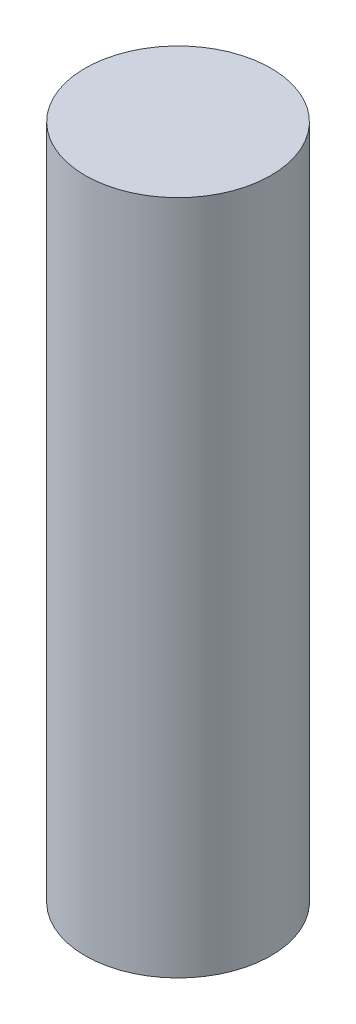
SolidWorks part; units mm, degrees
material "PBT General Purpose"
ref_plane "Front Plane" through (0, 0, 0) normal (0, 0, 1) x (1, 0, 0)
ref_plane "Top Plane" through (0, 0, 0) normal (0, 1, 0) x (1, 0, 0)
ref_plane "Right Plane" through (0, 0, 0) normal (1, 0, 0) x (0, 0, -1)
sketch "Sketch1" plane through (0, 0, 0) normal (0, 1, 0) x (1, 0, 0)
  circle A0 centre (0, 0) radius 27.5
extrude "Boss-Extrude1" add sketch "Sketch1" along normal blind 200
